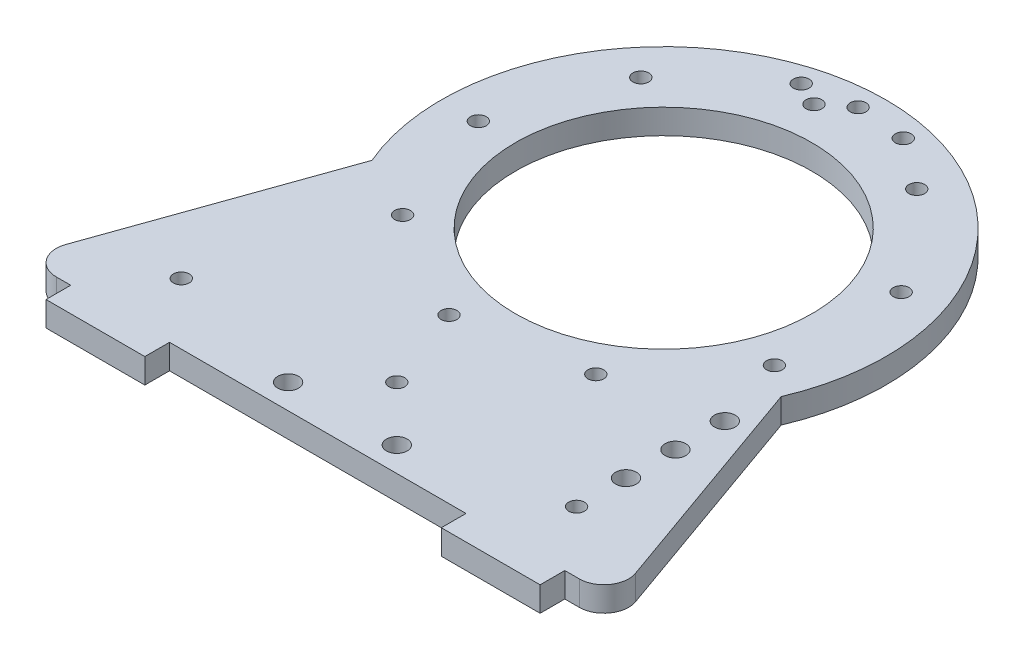
SolidWorks part; units mm, degrees
ref_plane "前视基准面" through (0, 0, 0) normal (0, 0, 1) x (1, 0, 0)
ref_plane "上视基准面" through (0, 0, 0) normal (0, 1, 0) x (1, 0, 0)
ref_plane "右视基准面" through (0, 0, 0) normal (1, 0, 0) x (0, 0, -1)
sketch "草图1" plane through (0, 0, 0) normal (0, 1, 0) x (1, 0, 0)
  line L0 (-60, 0) -> (-60, -70)
  line L1 (-60, -70) -> (60, -70)
  line L2 (60, -70) -> (60, 0)
  line L3 (0, 0) -> (0, 50000) construction
  arc A0 (60, 0) -> (0, 60) centre (0, 0) ccw
  circle A2 centre (-37.5, 0) radius 1.6
  circle A3 centre (0, 0) radius 37.5 construction
  circle A11 centre (-40, -57.62) radius 1.6
  circle A12 centre (40, -57.62) radius 1.6
  circle A13 centre (0, 0) radius 30
  arc A14 (0, 60) -> (-60, 0) centre (0, 0) ccw
  circle A17 centre (-28.7267, 24.1045) radius 1.6
  circle A18 centre (-6.5118, 36.9303) radius 1.6
  circle A19 centre (18.75, 32.476) radius 1.6
  circle A20 centre (35.2385, 12.8258) radius 1.6
  circle A21 centre (35.2385, -12.8258) radius 1.6
  circle A22 centre (18.75, -32.476) radius 1.6
  circle A23 centre (-6.5118, -36.9303) radius 1.6
  circle A24 centre (-28.7267, -24.1045) radius 1.6
  circle A25 centre (-11, -65) radius 2.1
  circle A27 centre (11, -65) radius 2.1
  circle A28 centre (40, -47.62) radius 2.1
  circle A29 centre (40, -37.62) radius 2.1
  circle A30 centre (40, -27.62) radius 2.1
  circle A31 centre (0, -54) radius 1.6
  circle A32 centre (8.4882, 40) radius 1.6
  circle A33 centre (-1.5118, 40.8627) radius 1.6
  circle A34 centre (-11.4207, 39.2634) radius 1.6
  point P27 (0, 0)
  point P45 (0, 0)
  point P49 (-11, 40)
  point P50 (-1.5118, 45.8093)
  point P51 (0, 0)
  point P56 (0, 0)
  dimension "D1" = 120
  dimension "D3" = 3.2
  dimension "D4" = 3.2
  dimension "D5" = 75
  dimension "D9" = 60
  dimension "D12" = 4.2
  dimension "D10" = 11
  dimension "D13" = 10
  dimension "D14" = 4.2
  dimension "D17" = 3.2
  dimension "D19" = 40
  dimension "D20" = 3.2
  dimension "D2" = 70
  dimension "D7" = 80
  dimension "D8" = 12.38
  dimension "D11" = 5
  dimension "D16" = 10
  dimension "D18" = 16
  dimension "D21" = 15
  dimension "D23" = 10
  dimension "D15" = 3
  dimension "D6" = 9
  dimension "D22" = 3
extrude "凸台-拉伸1" add sketch "草图1" along normal mid plane 5
sketch "草图2" plane through (0, 0, 70) normal (0, 0, 1) x (1, 0, 0)
  line L0 (0, 2.5) -> (0, -2.5) construction
  line L1 (-60, 2.5) -> (60, 2.5) construction
  line L2 (-60, -2.5) -> (60, -2.5) construction
  line L3 (50, -2.5) -> (30, -2.5)
  line L4 (-50, 2.5) -> (-30, 2.5)
  line L5 (-50, 2.5) -> (-50, -2.5)
  line L6 (-50, -2.5) -> (-30, -2.5)
  line L7 (-30, 2.5) -> (-30, -2.5)
  line L8 (30, 2.5) -> (30, -2.5)
  line L9 (50, 2.5) -> (30, 2.5)
  line L10 (50, 2.5) -> (50, -2.5)
  dimension "D1" = 30
  dimension "D2" = 20
extrude "凸台-拉伸2" add sketch "草图2" along normal blind 5
sketch "草图3" plane through (0, 2.5, 0) normal (0, 1, 0) x (1, 0, 0)
  line L0 (-41.407, -17.62) -> (-60, -70)
  line L1 (-60, -70) -> (-50, -70) construction
  line L2 (41.407, -17.62) -> (60, -70)
  line L3 (-60, 0) -> (-60, -70) construction
  line L4 (-60, -70) -> (-60, 0)
  line L5 (60, -70) -> (60, 0)
  arc A0 (41.407, -17.62) -> (-41.407, -17.62) centre (0, 0) ccw
  circle A1 centre (40, -27.62) radius 2.1 construction
  arc A2 (60, 0) -> (-60, 0) centre (0, 0) ccw
  arc M10 (60, 0) -> (-60, 0) centre (0, 0) ccw
  line M11 (-60, 0) -> (-60, -70)
  line M21 (60, -70) -> (60, 0)
  dimension "D1" = 45
  dimension "D2" = 10
extrude "切除-拉伸1" cut sketch "草图3" against normal through all contours A0 L2 L0 M21 M10 M11
fillet "圆角1" radius 5 2 edges at (-60, 0, 70) (60, 0, 70)
